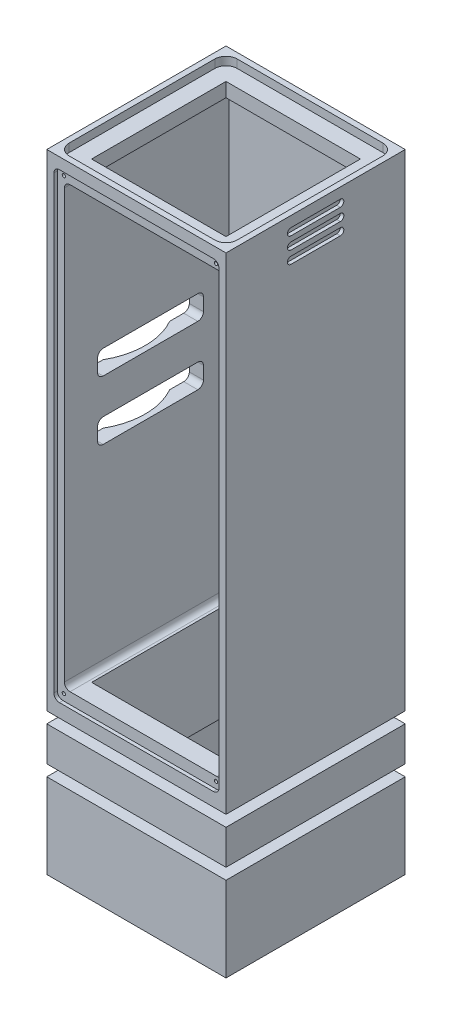
SolidWorks part; units mm, degrees
ref_plane "Front Plane" through (0, 0, 0) normal (0, 0, 1) x (1, 0, 0)
ref_plane "Top Plane" through (0, 0, 0) normal (0, 1, 0) x (1, 0, 0)
ref_plane "Right Plane" through (0, 0, 0) normal (1, 0, 0) x (0, 0, -1)
sketch "Sketch1" plane through (0, 0, 0) normal (0, 1, 0) x (1, 0, 0)
  line L0 (6.35, 44.45) -> (44.45, 44.45)
  line L1 (0, 0) -> (50.8, 0)
  line L2 (0, 0) -> (0, 50.8)
  line L3 (0, 50.8) -> (50.8, 50.8)
  line L4 (50.8, 0) -> (50.8, 50.8)
  line L5 (44.45, 6.35) -> (44.45, 44.45)
  line L6 (6.35, 6.35) -> (44.45, 6.35)
  line L7 (6.35, 6.35) -> (6.35, 44.45)
  dimension "D1" = 50.8
  dimension "D2" = 6.35
extrude "Boss-Extrude1" add sketch "Sketch1" along normal blind 178
sketch "Sketch2" plane through (0, 0, 0) normal (0, -1, 0) x (1, 0, 0)
  line L0 (47.8, -3) -> (3, -3)
  line L1 (3, -3) -> (3, -47.8)
  line L2 (3, -47.8) -> (47.8, -47.8)
  line L3 (47.8, -47.8) -> (47.8, -3)
  line L4 (6.35, -44.45) -> (44.45, -44.45)
  line L5 (6.35, -6.35) -> (6.35, -44.45)
  line L6 (44.45, -6.35) -> (6.35, -6.35)
  line L7 (44.45, -44.45) -> (44.45, -6.35)
  line L8 (6.35, -44.45) -> (44.45, -44.45)
  line L9 (6.35, -6.35) -> (6.35, -44.45)
  line L10 (44.45, -6.35) -> (6.35, -6.35)
  line L11 (44.45, -44.45) -> (44.45, -6.35)
  line L12 (0, -50.8) -> (0, 0) construction
  dimension "D2" = 3
  dimension "D1" = 0
extrude "Cut-Extrude1" cut sketch "Sketch2" against normal blind 20
sketch "Sketch3" plane through (0, 0, 0) normal (0, 0, 1) x (1, 0, 0)
  line L0 (0, 0) -> (50.8, 0) construction
  line L1 (2, 171.65) -> (48.8, 171.65)
  line L2 (2, 171.65) -> (2, 47.175)
  line L3 (2, 47.175) -> (48.8, 47.175)
  line L4 (48.8, 171.65) -> (48.8, 47.175)
  line L5 (0, 178) -> (0, 0) construction
  line L6 (50.8, 178) -> (50.8, 0) construction
  line L7 (0, 178) -> (50.8, 178) construction
  dimension "D1" = 47.175
  dimension "D2" = 2
  dimension "D3" = 2
  dimension "D4" = 6.35
extrude "Cut-Extrude2" cut sketch "Sketch3" against normal blind 47.625
sketch "Sketch4" plane through (0, 0, 0) normal (0, 0, 1) x (1, 0, 0)
  line L0 (0, 178) -> (0, 0) construction
  line L1 (0, 27.175) -> (50.8, 27.175)
  line L2 (0, 27.175) -> (0, 24)
  line L3 (0, 24) -> (50.8, 24)
  line L4 (50.8, 27.175) -> (50.8, 24)
  line L5 (50.8, 178) -> (50.8, 0) construction
  line L6 (0, 0) -> (50.8, 0) construction
  line L8 (0, 37) -> (50.8, 37)
  line L9 (0, 37) -> (0, 40.175)
  line L10 (0, 40.175) -> (50.8, 40.175)
  line L11 (50.8, 37) -> (50.8, 40.175)
  dimension "D1" = 24
  dimension "D2" = 3.175
  dimension "D3" = 13
extrude "Cut-Extrude3" cut sketch "Sketch4" against normal blind 3.175
sketch "Sketch5" plane through (0, 0, 0) normal (0, 0, 1) x (1, 0, 0)
  line L0 (50.8, 40.175) -> (0, 40.175) construction
  line L1 (0, 37) -> (3.175, 37)
  line L2 (0, 37) -> (0, 40.175)
  line L3 (0, 40.175) -> (3.175, 40.175)
  line L4 (3.175, 37) -> (3.175, 40.175)
  line L5 (0, 24) -> (50.8, 24) construction
  line L6 (0, 27.175) -> (3.175, 27.175)
  line L7 (0, 27.175) -> (0, 24)
  line L8 (0, 24) -> (3.175, 24)
  line L9 (3.175, 27.175) -> (3.175, 24)
  dimension "D1" = 3.175
extrude "Cut-Extrude4" cut sketch "Sketch5" against normal through all
ref_plane "Plane1" through (0, 0, -25.4) normal (0, 0, 1) x (1, 0, 0)
ref_plane "Plane2" through (25.4, 0, 0) normal (-1, 0, 0) x (0, 0, 1)
sketch "Sketch6" plane through (0, 0, 0) normal (-1, 0, 0) x (0, 0, 1)
  line L0 (-32.4, 174) -> (-18.4, 174) construction
  line L1 (-32.4, 175) -> (-18.4, 175)
  line L2 (-32.4, 173) -> (-18.4, 173)
  line L3 (-32.4, 170.5) -> (-18.4, 170.5) construction
  line L4 (-32.4, 171.5) -> (-18.4, 171.5)
  line L5 (-32.4, 169.5) -> (-18.4, 169.5)
  line L6 (-32.4, 167) -> (-18.4, 167) construction
  line L9 (-32.4, 168) -> (-18.4, 168)
  line L10 (-32.4, 166) -> (-18.4, 166)
  line L11 (-25.4, 174) -> (-25.4, 170.5) construction
  line L12 (-25.4, 170.5) -> (-25.4, 167) construction
  line L13 (-25.4, 174) -> (-25.4, 178) construction
  line L14 (-50.8, 178) -> (0, 178) construction
  arc A0 (-32.4, 175) -> (-32.4, 173) centre (-32.4, 174) ccw
  arc A1 (-18.4, 173) -> (-18.4, 175) centre (-18.4, 174) ccw
  arc A2 (-32.4, 171.5) -> (-32.4, 169.5) centre (-32.4, 170.5) ccw
  arc A3 (-18.4, 169.5) -> (-18.4, 171.5) centre (-18.4, 170.5) ccw
  arc A6 (-32.4, 168) -> (-32.4, 166) centre (-32.4, 167) ccw
  arc A7 (-18.4, 166) -> (-18.4, 168) centre (-18.4, 167) ccw
  point P2 (-25.4, 174)
  point P9 (-25.4, 170.5)
  point P16 (-25.4, 167)
  point P25 (-33.4, 167)
  point P26 (-17.4, 167)
  dimension "D1" = 3.5
  dimension "D2" = 2
  dimension "D3" = 4
  dimension "D4" = 16
extrude "Cut-Extrude5" cut sketch "Sketch6" against normal blind 1
mirror "Mirror1" about plane through (0, 0, -25.4) normal (0, 0, 1) of "Cut-Extrude3"
mirror "Mirror2" about plane through (25.4, 0, 0) normal (-1, 0, 0) of "Cut-Extrude5", "Cut-Extrude4"
sketch "Sketch7" plane through (0, 0, 0) normal (0, 0, 1) x (1, 0, 0)
  line L0 (0, 178) -> (50.8, 178) construction
  line L1 (2, 171.65) -> (48.8, 171.65)
  line L2 (2, 171.65) -> (2, 174.825)
  line L3 (2, 174.825) -> (48.8, 174.825)
  line L4 (48.8, 171.65) -> (48.8, 174.825)
  line L6 (2, 47.175) -> (48.8, 47.175)
  line L7 (2, 47.175) -> (2, 44)
  line L8 (2, 44) -> (48.8, 44)
  line L9 (48.8, 47.175) -> (48.8, 44)
  dimension "D1" = 3.175
extrude "Cut-Extrude6" cut sketch "Sketch7" against normal blind 1
fillet "Fillet1" radius 1.5875 12 edges at (47.8, 10, -47.8) (47.8, 10, -3) (3, 10, -47.8) (3, 10, -3) (48.8, 47.175, -24.3125) (2, 47.175, -24.3125) (48.8, 171.65, -24.3125) (2, 171.65, -24.3125) (48.8, 174.825, -0.5) (2, 174.825, -0.5) (48.8, 44, -0.5) (2, 44, -0.5)
sketch "Sketch8" plane through (0, 178, 0) normal (0, 1, 0) x (1, 0, 0)
  line L0 (0, 50.8) -> (0, 0) construction
  line L1 (4.7625, 49.2125) -> (46.0375, 49.2125)
  line L2 (1.5875, 46.0375) -> (1.5875, 4.7625)
  line L3 (4.7625, 1.5875) -> (46.0375, 1.5875)
  line L4 (49.2125, 46.0375) -> (49.2125, 4.7625)
  line L5 (50.8, 50.8) -> (0, 50.8) construction
  line L6 (0, 0) -> (50.8, 0) construction
  arc A0 (46.0375, 49.2125) -> (49.2125, 46.0375) centre (46.0375, 46.0375) cw
  arc A1 (49.2125, 4.7625) -> (46.0375, 1.5875) centre (46.0375, 4.7625) cw
  arc A2 (4.7625, 1.5875) -> (1.5875, 4.7625) centre (4.7625, 4.7625) cw
  arc A3 (1.5875, 46.0375) -> (4.7625, 49.2125) centre (4.7625, 46.0375) cw
  dimension "D1" = 3.175
  dimension "D2" = 1.5875
  dimension "D3" = 1.5875
  dimension "D4" = 1.5875
extrude "Cut-Extrude7" cut sketch "Sketch8" against normal blind 2.3444
hole_wizard "M1.2x0.25 Tapped Hole1" positions "Sketch12" profile "Sketch14" tap size "M1.2x0.25" standard "ANSI Metric"
sketch "Sketch12" plane through (0, 0, -1) normal (0, 0, 1) x (1, 0, 0)
  line L0 (2, 48.7625) -> (2, 45.5875) construction
  line L1 (3.5875, 44) -> (47.2125, 44) construction
  line L2 (3.8415, 172.9838) -> (3.8415, 45.8415) construction
  line L3 (3.8415, 45.8415) -> (46.9588, 45.8415) construction
  line L4 (46.9588, 45.8415) -> (46.9588, 172.9838) construction
  line L5 (46.9588, 172.9838) -> (3.8415, 172.9838) construction
  line L6 (47.2125, 174.825) -> (3.5875, 174.825) construction
  line L7 (48.8, 45.5875) -> (48.8, 173.2375) construction
  point P0 (3.8415, 172.9838)
  point P3 (46.9588, 172.9838)
  point P6 (3.8415, 45.8415)
  point P9 (46.9588, 45.8415)
  dimension "D1" = 1.8415
  dimension "D2" = 1.8415
  dimension "D3" = 1.8412
  dimension "D4" = 1.8412
sketch "Sketch14" plane through (3.8415, 172.9838, -1) normal (1, 0, 0) x (0, -1, 0)
  line L0 (0, 0) -> (0, 3.2851)
  line L1 (0, 3.2851) -> (0.475, 2.9997)
  line L2 (0.475, 2.9997) -> (0.475, 0)
  line L5 (0.475, 0) -> (0, 0)
  line L10 (0, 3.2851) -> (-0.475, 2.9997) construction
  line L11 (0, -6.35) -> (0, 107.95) construction
  dimension "Tap Drill Dia." = 0.95
  dimension "Tap Drill Depth" = 2.9997
  dimension "Drill Angle" = 118
cosmetic thread "Hole Thread5" parameters "D1"=2.4, "D2"=1.2
cosmetic thread "Hole Thread6" parameters "D1"=2.4, "D2"=1.2
cosmetic thread "Hole Thread7" parameters "D1"=2.4, "D2"=1.2
cosmetic thread "Hole Thread8" parameters "D1"=2.4, "D2"=1.2
sketch "Sketch17" plane through (0, 0, -1) normal (0, 0, 1) x (1, 0, 0)
  line L0 (2, 170.0625) -> (2, 48.7625) construction
  line L1 (2, 170.0625) -> (2, 48.7625)
  line L2 (4, 170.0625) -> (4, 48.7625)
  line L3 (3.5875, 47.175) -> (47.2125, 47.175) construction
  line L4 (47.2125, 47.175) -> (3.5875, 47.175) construction
  line L5 (47.2125, 171.65) -> (3.5875, 171.65) construction
  line L6 (3.5875, 171.65) -> (47.2125, 171.65) construction
  line L7 (3.5875, 171.65) -> (5.5875, 171.65)
  line L8 (3.5875, 47.175) -> (5.5875, 47.175)
  arc A0 (2, 48.7625) -> (3.5875, 47.175) centre (3.5875, 48.7625) ccw construction
  arc A1 (3.5875, 171.65) -> (2, 170.0625) centre (3.5875, 170.0625) ccw construction
  arc A2 (2, 48.7625) -> (3.5875, 47.175) centre (3.5875, 48.7625) ccw
  arc A3 (3.5875, 171.65) -> (2, 170.0625) centre (3.5875, 170.0625) ccw
  arc A4 (4, 48.7625) -> (5.5875, 47.175) centre (5.5875, 48.7625) ccw
  arc A5 (5.5875, 171.65) -> (4, 170.0625) centre (5.5875, 170.0625) ccw
  dimension "D1" = 2
extrude "Boss-Extrude2" add sketch "Sketch17" against normal up to next
sketch "Sketch15" plane through (0, 0, 0) normal (-1, 0, 0) x (0, 0, 1)
  line L0 (-50.8, 0) -> (0, 0) construction
  line L3 (-25.4, 101.6) -> (-25.4, 40.175) construction
  line L7 (-47.625, 40.175) -> (-3.175, 40.175) construction
  line L11 (-40.4, 108.4) -> (-10.4, 108.4)
  line L12 (-40.4, 108.4) -> (-40.4, 101.6)
  line L13 (-40.4, 101.6) -> (-10.4, 101.6)
  line L14 (-10.4, 108.4) -> (-10.4, 101.6)
  line L15 (-40.4, 125.2) -> (-10.4, 125.2)
  line L16 (-40.4, 125.2) -> (-40.4, 118.4)
  line L17 (-40.4, 118.4) -> (-10.4, 118.4)
  line L18 (-10.4, 125.2) -> (-10.4, 118.4)
  dimension "D1" = 101.6
  dimension "D5" = 30
  dimension "D6" = 6.8
  dimension "D7" = 10
extrude "Cut-Extrude8" cut sketch "Sketch15" against normal up to next
fillet "Fillet2" radius 1.5875 8 edges at (2, 101.6, -10.4) (2, 101.6, -40.4) (2, 108.4, -40.4) (2, 108.4, -10.4) (2, 118.4, -10.4) (2, 125.2, -10.4) (2, 118.4, -40.4) (2, 125.2, -40.4)
ref_plane "Plane4" through (0, 113.4, 0) normal (0, 1, 0) x (1, 0, 0)
sketch "Sketch20" plane through (0, 113.4, 0) normal (0, 1, 0) x (1, 0, 0)
  line L0 (-16.55, 25.4) -> (0, 25.4) construction
  line L1 (0, 38.8125) -> (0, 11.9875) construction
  circle A0 centre (-16.55, 25.4) radius 19.05
  point P3 (2.5, 25.4)
  dimension "D2" = 38.1
  dimension "D1" = 2.5
extrude "Cut-Extrude9" cut sketch "Sketch20" against normal blind 21.8 and the other way blind 21.8 contours A0
